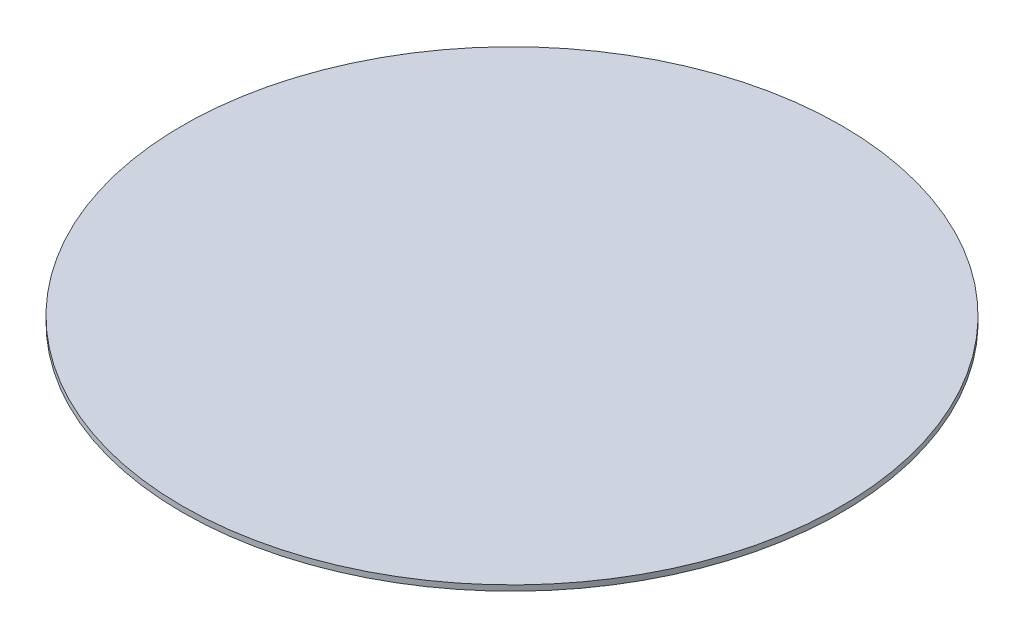
SolidWorks part; units mm, degrees
material "AISI 1020"
ref_plane "Front Plane" through (0, 0, 0) normal (0, 0, 1) x (1, 0, 0)
ref_plane "Top Plane" through (0, 0, 0) normal (0, 1, 0) x (1, 0, 0)
ref_plane "Right Plane" through (0, 0, 0) normal (1, 0, 0) x (0, 0, -1)
sketch "Sketch2" plane through (0, 0, 0) normal (0, 1, 0) x (1, 0, 0)
  circle A0 centre (0, 0) radius 304.8
  dimension "D1" = 609.6
extrude "Boss-Extrude1" add sketch "Sketch2" along normal blind 5.08
